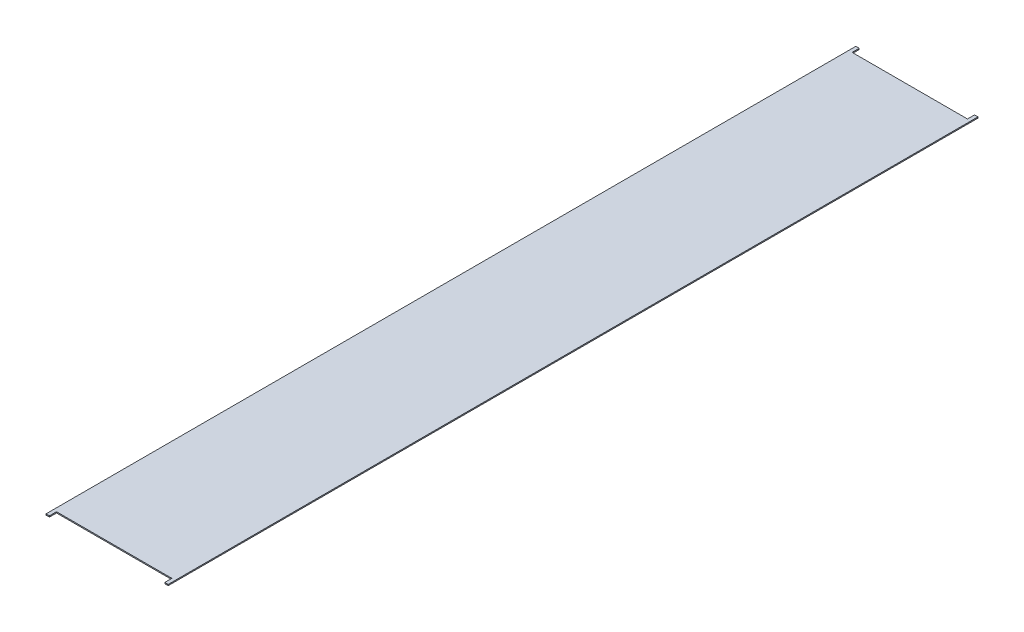
SolidWorks part; units mm, degrees
ref_plane "Plan de face" through (0, 0, 0) normal (0, 0, 1) x (1, 0, 0)
ref_plane "Plan de dessus" through (0, 0, 0) normal (0, 1, 0) x (1, 0, 0)
ref_plane "Plan de droite" through (0, 0, 0) normal (1, 0, 0) x (0, 0, -1)
sketch "Esquisse1" plane through (0, 0, 0) normal (0, 0, 1) x (1, 0, 0)
  line L9 (-20, 39) -> (410, 39)
  line L10 (-20, 35) -> (410, 35)
  line L30 (-20, 39) -> (-20, 35)
  line L33 (410, 39) -> (410, 35)
  dimension "D2" = 4
  dimension "D3" = 430
extrude "Boss.-Extru.1" add sketch "Esquisse1" along normal blind 2850
sketch "Esquisse10" plane through (0, 35, 0) normal (0, -1, 0) x (1, 0, 0)
  line L0 (-20, 0) -> (410, 0) construction
  line L1 (-8, 0) -> (398, 0)
  line L2 (-8, 0) -> (-8, 25)
  line L3 (-8, 25) -> (398, 25)
  line L4 (398, 0) -> (398, 25)
  line L5 (-20, 2850) -> (-20, 0) construction
  line L6 (410, 2850) -> (410, 0) construction
  line L7 (-20, 1425) -> (1349.8187, 1425) construction
  line L8 (398, 2850) -> (398, 2825)
  line L9 (-8, 2825) -> (398, 2825)
  line L10 (-8, 2850) -> (-8, 2825)
  line L11 (-8, 2850) -> (398, 2850)
  dimension "D1" = 25
  dimension "D2" = 12
  dimension "D3" = 12
extrude "Enlèv. mat.-Extru.1" cut sketch "Esquisse10" against normal through all
